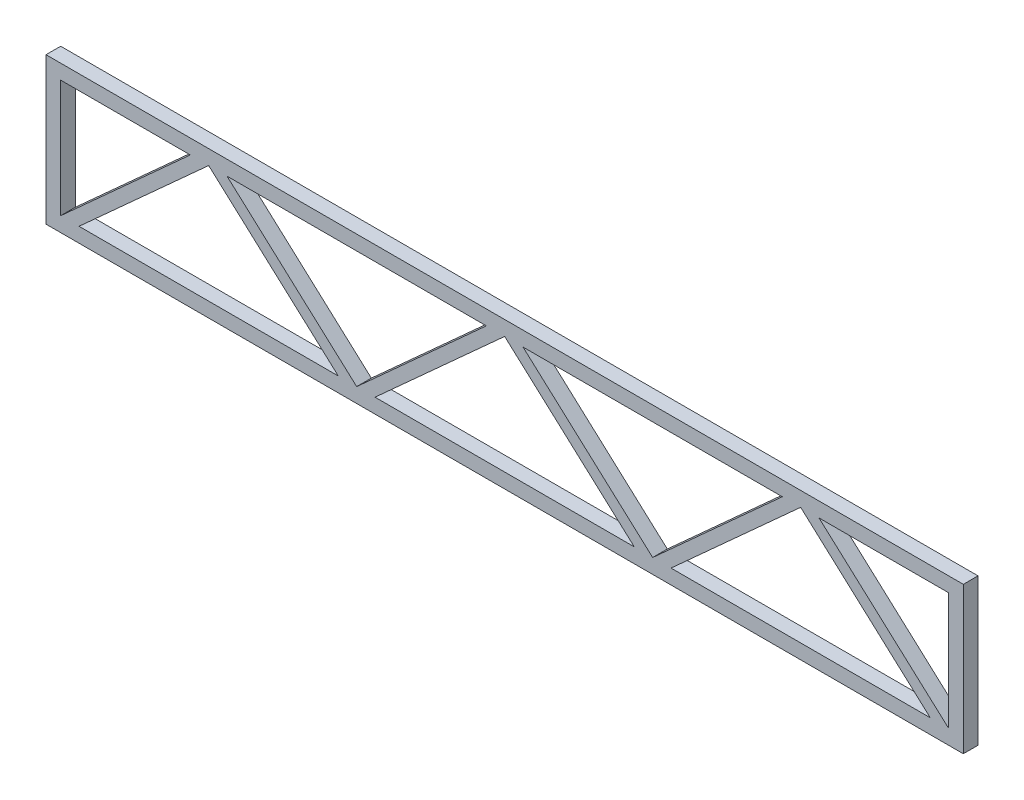
SolidWorks part; units mm, degrees
material "轻木"
ref_plane "前视基准面" through (0, 0, 0) normal (0, 0, 1) x (1, 0, 0)
ref_plane "上视基准面" through (0, 0, 0) normal (0, 1, 0) x (1, 0, 0)
ref_plane "右视基准面" through (0, 0, 0) normal (1, 0, 0) x (0, 0, -1)
other "Configuration Table"
sketch "草图1" plane through (0, 0, 0) normal (0, 0, 1) x (1, 0, 0)
  line L0 (-121, 16) -> (121, 16)
  line L1 (-125, 20) -> (125, 20)
  line L2 (-125, 20) -> (-125, -20)
  line L3 (-125, -20) -> (125, -20)
  line L4 (125, 20) -> (125, -20)
  line L5 (-125, 20) -> (125, -20) construction
  line L6 (-125, -20) -> (125, 20) construction
  line L7 (121, 16) -> (121, -16)
  line L8 (-121, -16) -> (121, -16)
  line L9 (-121, 16) -> (-121, -16)
  line L10 (-121, -16) -> (-85.6667, 16)
  line L11 (-116, -16) -> (-80.6667, 16)
  line L12 (-75.6667, 16) -> (-40.3333, -16)
  line L13 (-80.6667, 16) -> (-45.3333, -16)
  line L14 (-35.3333, -16) -> (0, 16)
  line L15 (-40.3333, -16) -> (-5, 16)
  line L16 (0, 0) -> (0, -16) construction
  line L17 (35.3333, -16) -> (0, 16)
  line L18 (40.3333, -16) -> (5, 16)
  line L19 (75.6667, 16) -> (40.3333, -16)
  line L20 (80.6667, 16) -> (45.3333, -16)
  line L21 (116, -16) -> (80.6667, 16)
  line L22 (121, -16) -> (85.6667, 16)
  point P0 (0, 0)
  dimension "D1" = 40
  dimension "D2" = 250
  dimension "D4" = 5
  dimension "D5" = 5
  dimension "D6" = 5
  dimension "D3" = 4
extrude "凸台-拉伸1" add sketch "草图1" along normal blind 4 contours L4 L1 L2 L3 L9 L0 L7 L8 | L8 L11 L0 L10 | L0 L13 L8 L12 | L15 L8 L14 L0 | L8 L18 L0 L17 | L20 L0 L19 L8 | L8 L22 L0 L21
